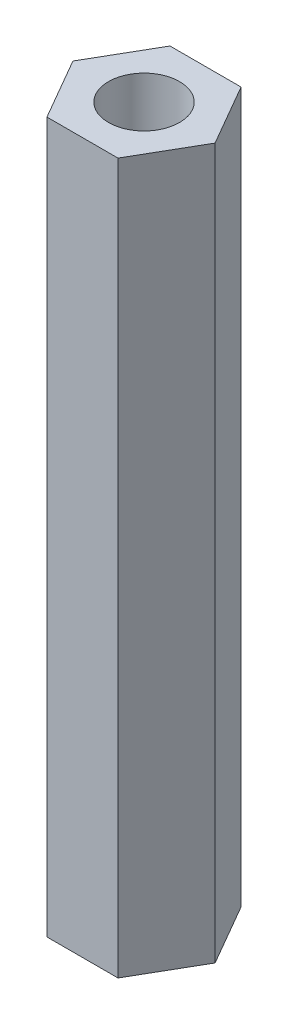
SolidWorks part; units mm, degrees
ref_plane "정면" through (0, 0, 0) normal (0, 0, 1) x (1, 0, 0)
ref_plane "윗면" through (0, 0, 0) normal (0, 1, 0) x (1, 0, 0)
ref_plane "우측면" through (0, 0, 0) normal (1, 0, 0) x (0, 0, -1)
sketch "스케치1" plane through (0, 0, 0) normal (0, 1, 0) x (1, 0, 0)
  line L1 (1.5011, 2.6) -> (-1.5011, 2.6)
  line L2 (-1.5011, 2.6) -> (-3.0022, 0)
  line L3 (-3.0022, 0) -> (-1.5011, -2.6)
  line L4 (-1.5011, -2.6) -> (1.5011, -2.6)
  line L5 (1.5011, -2.6) -> (3.0022, 0)
  line L6 (3.0022, 0) -> (1.5011, 2.6)
  circle A0 centre (0, 0) radius 2.6 construction
  circle A1 centre (0, 0) radius 1.5
  dimension "D2" = 3
  dimension "D1" = 5.2
extrude "보스-돌출1" add sketch "스케치1" along normal blind 30
